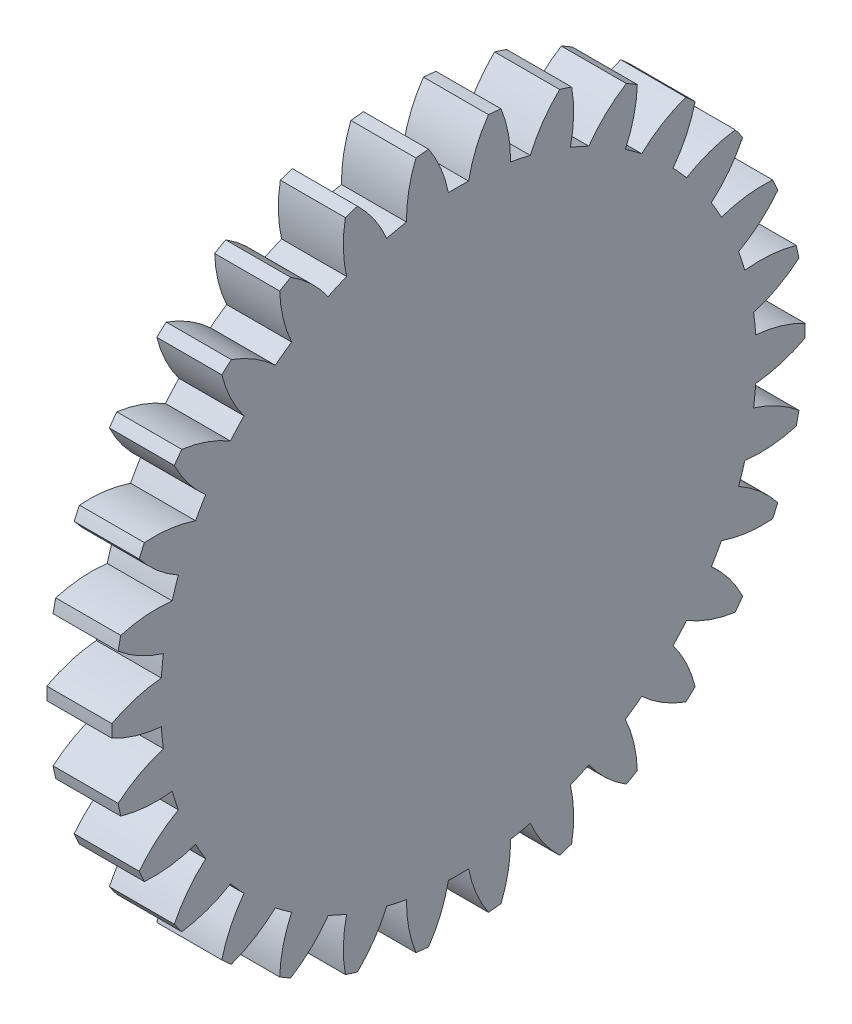
SolidWorks part; units mm, degrees
material "ﾎﾟﾘｵｷｼﾒﾁﾚﾝ(POM)ｱｾﾀｰﾙ共重合体"
ref_plane "Plane1" through (0, 0, 0) normal (0, 0, 1) x (1, 0, 0)
ref_plane "Plane2" through (0, 0, 0) normal (0, 1, 0) x (1, 0, 0)
ref_plane "Plane3" through (0, 0, 0) normal (1, 0, 0) x (0, 0, -1)
other "Configuration Table"
sketch "HoldingSke" plane through (0, 0, 0) normal (0, 1, 0) x (1, 0, 0)
  line L0 (0, 0) -> (0.866, -0.5)
  line L1 (-15, 0) -> (100, 0) construction
  line L2 (0, 0) -> (-2.1039, 2.3779)
  line L3 (0, 0) -> (-11.863, 4.5341)
  line L4 (0, 0) -> (7.479, 4.318)
  line L5 (0, 0) -> (-46.8476, -17.4728)
  line L6 (0, 0) -> (-2.4869, -1.6779)
  line L7 (-2.1039, 2.3779) -> (8.6586, 51.2059)
  line L8 (-76.2, 54.61) -> (-75.2, 54.61)
  line L9 (-71.009, 38.7566) -> (-53.1078, 45.2721)
  line L10 (-76.2, 71.12) -> (104.1128, 71.12)
  line L11 (0, 0) -> (-3, 0)
  line L12 (-76.2, 101.6) -> (-76.162, 101.6)
  line L13 (24.9733, 27.94) -> (52.9518, 28.4284)
  line L14 (24.9733, 27.94) -> (24.9743, 27.94)
  line L15 (24.9733, 27.94) -> (100.4006, 29.5858)
  line L16 (-63.627, -1) -> (-12.827, -1)
  circle A0 centre (0, 0) radius 4
  circle A1 centre (0, 0) radius 13.749
  circle A2 centre (0, 0) radius 37.5
  circle A3 centre (0, 0) radius 4
  dimension "MHD" = 27.498
  dimension "Hub_dia" = 75
  dimension "Bore" = 8
  dimension "MBD" = 8
  dimension "Num_teeth" = 30
  dimension "Pitch" = 1
  dimension "Overall_len" = 50
  dimension "Show_teeth" = 30
  dimension "Thickness" = 3
  dimension "OAL" = 50.0001
  dimension "T_dim" = 1
  dimension "Ap" = 20
  dimension "H" = 19.05
  dimension "Pitch_radius" = 180.3128
  dimension "Width" = 3
  dimension "Backlash" = 0.038
  dimension "Addendum_fac" = 1
  dimension "Dedendum_fac" = 1.25
  dimension "Clearance_fac" = 0.25
  dimension "Dedendum_add" = 0.001
  dimension "Module" = 1
sketch "BasProSke" plane through (0, 0, 0) normal (0, 1, 0) x (1, 0, 0)
  line L0 (-10, 0) -> (60, 0) construction
  line L1 (0, 0) -> (0, 16)
  line L2 (0, 0) -> (3, 0)
  line L3 (3, 0) -> (3, 16)
  line L4 (3, 16) -> (0, 16)
  dimension "Thickness" = 3
  dimension "Diameter" = 32
revolve "Base-Revolve" add sketch "BasProSke" angle 360 about L0
sketch "TooCutSke" plane through (0, 0, 0) normal (1, 0, 0) x (0, 0, -1)
  line L1 (0, 0) -> (0, 107) construction
  line L2 (0, 0) -> (-0.8515, 14.9758) construction
  line L3 (0, 0) -> (-3.1323, 29.8014) construction
  line L4 (-0.8515, 14.9758) -> (-1.5661, 14.9007) construction
  arc A0 (0.4664, 13.7411) -> (-0.4664, 13.7411) centre (0, 0) ccw
  arc A1 (1.3975, 15.9644) -> (-1.3975, 15.9644) centre (0, 0) ccw
  circle A2 centre (0, 0) radius 15 construction
  circle A3 centre (0, 0) radius 14.0954 construction
  arc A4 (-0.4664, 13.7411) -> (-1.3975, 15.9644) centre (-6.3534, 12.5823) ccw
  arc A5 (1.3975, 15.9644) -> (0.4664, 13.7411) centre (6.3534, 12.5823) ccw
  dimension "Root_dia" = 27.498
  dimension "Overcut_dia" = 32.0508
  dimension "Pitch_dia" = 30
  dimension "Base_dia" = 28.1908
  dimension "Flank_rad" = 6
  dimension "Half_ang" = 6
  dimension "Half_CT" = 0.7185
extrude "ToothCut" cut sketch "TooCutSke" along normal through all
fillet "Breaks" [suppressed] radius 0.02
fillet "RootFillets" [suppressed] radius 0.251
pattern_circular "TeethCuts" count 30 every 12 about axis through (-10, 0, 0) along (1, 0, 0) of "ToothCut", "RootFillets", "Breaks"
sketch "HubNeaOneSke" plane through (0, 0, 0) normal (-1, 0, 0) x (0, 0, 1)
  circle A0 centre (0, 0) radius 13.749
  dimension "Diameter" = 27.498
extrude "HubNearOne" [suppressed] add sketch "HubNeaOneSke" along normal blind 47.0001
sketch "HubNeaBotSke" plane through (0, 0, 0) normal (-1, 0, 0) x (0, 0, 1)
  circle A0 centre (0, 0) radius 13.749
  dimension "Diameter" = 27.498
extrude "HubNearBoth" [suppressed] add sketch "HubNeaBotSke" along normal blind 23.5
ref_plane "FarPln" through (3, 0, 0) normal (1, 0, 0) x (0, 0, -1)
sketch "HubFarSke" plane through (3, 0, 0) normal (1, 0, 0) x (0, 0, -1)
  circle A0 centre (0, 0) radius 13.749
  dimension "Diameter" = 27.498
extrude "HubFar" [suppressed] add sketch "HubFarSke" along normal blind 23.5
sketch "BorSke" plane through (0, 0, 0) normal (1, 0, 0) x (0, 0, -1)
  circle A0 centre (0, 0) radius 4
  dimension "Diameter" = 8
extrude "Bore" cut sketch "BorSke" along normal mid plane 100.0001
sketch "KeySke" plane through (0, 0, 0) normal (1, 0, 0) x (0, 0, -1)
  line L0 (-1, 0) -> (-1, 5)
  line L1 (-1, 5) -> (1, 5)
  line L2 (1, 5) -> (1, 0)
  line L3 (0, 0) -> (0, 34) construction
  line L4 (-1, 0) -> (1, 0)
  dimension "Offset" = 5
  dimension "Width" = 2
extrude "Keyway" [suppressed] cut sketch "KeySke" along normal mid plane 100.0001
pattern_circular "Keyway2" [suppressed] count 2 every 90 about axis through (-10, 0, 0) along (1, 0, 0)
sketch "ｽｹｯﾁ1" plane through (0, 0, 0) normal (-1, 0, 0) x (0, 0, 1)
  circle A0 centre (0, 0) radius 4 construction
  circle A1 centre (0, 0) radius 4
extrude "ﾎﾞｽ - 押し出し1" add sketch "ｽｹｯﾁ1" against normal up to surface (3 mm away) up to face at (3, 0, 4)
equation "' \"Module@HoldingSke\" = 6.35"
equation "' \"Num_teeth@HoldingSke\" = 12"
equation "' \"Ap@HoldingSke\" =  20"
equation "' \"Ap@HoldingSke\" = 20"
equation "' \"Width@HoldingSke\" = 0.5 * 25.4"
equation "' \"Hub_dia@HoldingSke\"= 1 * 25.4"
equation "' \"Hub_dia@HoldingSke\" = 1 * 25.4"
equation "' \"Overall_len@HoldingSke\" = 1.0 * 25.4"
equation "' \"Bore@HoldingSke\" = 0.75 * 25.4"
equation "' \"T_dim@HoldingSke\" = 0.1 * 25.4"
equation "' \"Width@KeySke\" = 0.25 * 25.4"
equation "' \"Show_teeth@HoldingSke\" = 13"
equation "' \"Backlash@HoldingSke\" = 0.009 * 25.4"
equation "' \"Addendum_fac@HoldingSke\" = 1.0"
equation "' \"Dedendum_fac@HoldingSke\" = 1.25"
equation "' \"Dedendum_add@HoldingSke\" = 0.00005 * 25.4"
equation "' \"Clearance_fac@HoldingSke\" = 0.25"
equation "\"Pitch@HoldingSke\" = 1 / \"Module@HoldingSke\""
equation "\"Overcut_dia@TooCutSke\" = (\"Num_teeth@HoldingSke\" + 2 * \"Addendum_fac@HoldingSke\") / \"Pitch@HoldingSke\" + 0.002 * 25.4"
equation "\"Pitch_dia@TooCutSke\" = \"Num_teeth@HoldingSke\" / \"Pitch@HoldingSke\""
equation "\"Base_dia@TooCutSke\" = \"Num_teeth@HoldingSke\" / \"Pitch@HoldingSke\" * cos((\"Ap@HoldingSke\"  * 3.14159265 / 180))"
equation "\"Root_dia@TooCutSke\" = (\"Num_teeth@HoldingSke\" + 2) / \"Pitch@HoldingSke\" - 2 * (\"Addendum_fac@HoldingSke\" + \"Dedendum_fac@HoldingSke\") / \"Pitch@HoldingSke\" - \"Dedendum_add@HoldingSke\" * 2"
equation "\"Half_ang@TooCutSke\" = 180 / \"Num_teeth@HoldingSke\""
equation "\"Half_CT@TooCutSke\" = \"Num_teeth@HoldingSke\" / \"Pitch@HoldingSke\" * sin((3.14159265 / 2 / \"Num_teeth@HoldingSke\")) / 2 - 7 * \"Backlash@HoldingSke\" / 4"
equation "\"Flank_rad@TooCutSke\" = \"Num_teeth@HoldingSke\" / \"Pitch@HoldingSke\" / 5"
equation "\"Radius@RootFillets\" = \"Clearance_fac@HoldingSke\" / \"Pitch@HoldingSke\" + \"Dedendum_add@HoldingSke\""
equation "\"Break_rad@Breaks\" = 0.02 / \"Pitch@HoldingSke\""
equation "\"Thickness@HoldingSke\" = \"Width@HoldingSke\""
equation "\"OAL@HoldingSke\" = \"Thickness@HoldingSke\""
equation "\"MHD@HoldingSke\" = (\"Num_teeth@HoldingSke\" + 2) / \"Pitch@HoldingSke\" - 2 * (\"Addendum_fac@HoldingSke\" + \"Dedendum_fac@HoldingSke\")  / \"Pitch@HoldingSke\" - \"Dedendum_add@HoldingSke\" * 2"
equation "\"MBD@HoldingSke\" = (\"Num_teeth@HoldingSke\" + 2) / \"Pitch@HoldingSke\" - 2 * (\"Addendum_fac@HoldingSke\" + \"Dedendum_fac@HoldingSke\")  / \"Pitch@HoldingSke\" - \"Dedendum_add@HoldingSke\" * 2 - 0.002 * 25.4"
equation "\"MHD@HoldingSke\" = ((sgn( \"MHD@HoldingSke\" - \"Hub_dia@HoldingSke\" )-1)*( \"MHD@HoldingSke\" - \"Hub_dia@HoldingSke\" ))/-2+ \"Hub_dia@HoldingSke\""
equation "\"MBD@HoldingSke\" = ((sgn( \"MBD@HoldingSke\" - \"Bore@HoldingSke\" )-1)*( \"MBD@HoldingSke\" - \"Bore@HoldingSke\" ))/-2+ \"Bore@HoldingSke\""
equation "\"OAL@HoldingSke\" = ((sgn( \"OAL@HoldingSke\" - \"Overall_len@HoldingSke\" )+1)*( \"OAL@HoldingSke\" - \"Overall_len@HoldingSke\" ))/2 + \"Overall_len@HoldingSke\" + 0.000002 * 25.4"
equation "\"Num_teeth@TeethCuts\" = int( \"Show_teeth@HoldingSke\" ) + 1"
equation "\"Num_teeth@TeethCuts\" = ((sgn( \"Num_teeth@TeethCuts\" - \"Num_teeth@HoldingSke\" )-1)*( \"Num_teeth@TeethCuts\" - \"Num_teeth@HoldingSke\" ))/-2+ \"Num_teeth@HoldingSke\""
equation "\"Num_teeth@TeethCuts\" = ((sgn( \"Num_teeth@TeethCuts\" - 2.0)+1)*( \"Num_teeth@TeethCuts\" - 2.0))/2 +2.0"
equation "\"Angle@TeethCuts\" = 360.0 / \"Num_teeth@HoldingSke\""
equation "\"Diameter@BasProSke\" = (\"Num_teeth@HoldingSke\" + 2 * \"Addendum_fac@HoldingSke\") / \"Pitch@HoldingSke\""
equation "\"Thickness@BasProSke\"  = \"Thickness@HoldingSke\""
equation "' \"Fillet_rad@BasProSke\" =  \"Thickness@HoldingSke\" * 0.05"
equation "' \"Fillet_rad@BasProSke\" = \"Thickness@HoldingSke\" * 0.05"
equation "\"MHD@HoldingSke\" = ((sgn( \"MHD@HoldingSke\" - \"Root_dia@TooCutSke\" )-1)*( \"MHD@HoldingSke\" - \"Root_dia@TooCutSke\" ))/-2+ \"Root_dia@TooCutSke\""
equation "\"Diameter@HubNeaOneSke\" = \"MHD@HoldingSke\""
equation "\"Length@HubNearOne\" = \"OAL@HoldingSke\" - \"Thickness@BasProSke\""
equation "\"Diameter@HubNeaBotSke\" = \"MHD@HoldingSke\""
equation "\"Length@HubNearBoth\" = ( \"OAL@HoldingSke\" - \"Thickness@BasProSke\" ) / 2.0"
equation "\"Thickness@FarPln\" = \"Thickness@BasProSke\""
equation "\"Diameter@HubFarSke\" = \"MHD@HoldingSke\""
equation "\"Length@HubFar\" = ( \"OAL@HoldingSke\" - \"Thickness@BasProSke\" ) / 2.0"
equation "\"Diameter@BorSke\" = \"MBD@HoldingSke\""
equation "\"D1@Bore\" = \"OAL@HoldingSke\" * 2.0"
equation "\"D1@Keyway\" = \"OAL@HoldingSke\" * 2.0"
equation "\"Offset@KeySke\" = \"T_dim@HoldingSke\" + \"MBD@HoldingSke\" / 2.0"
